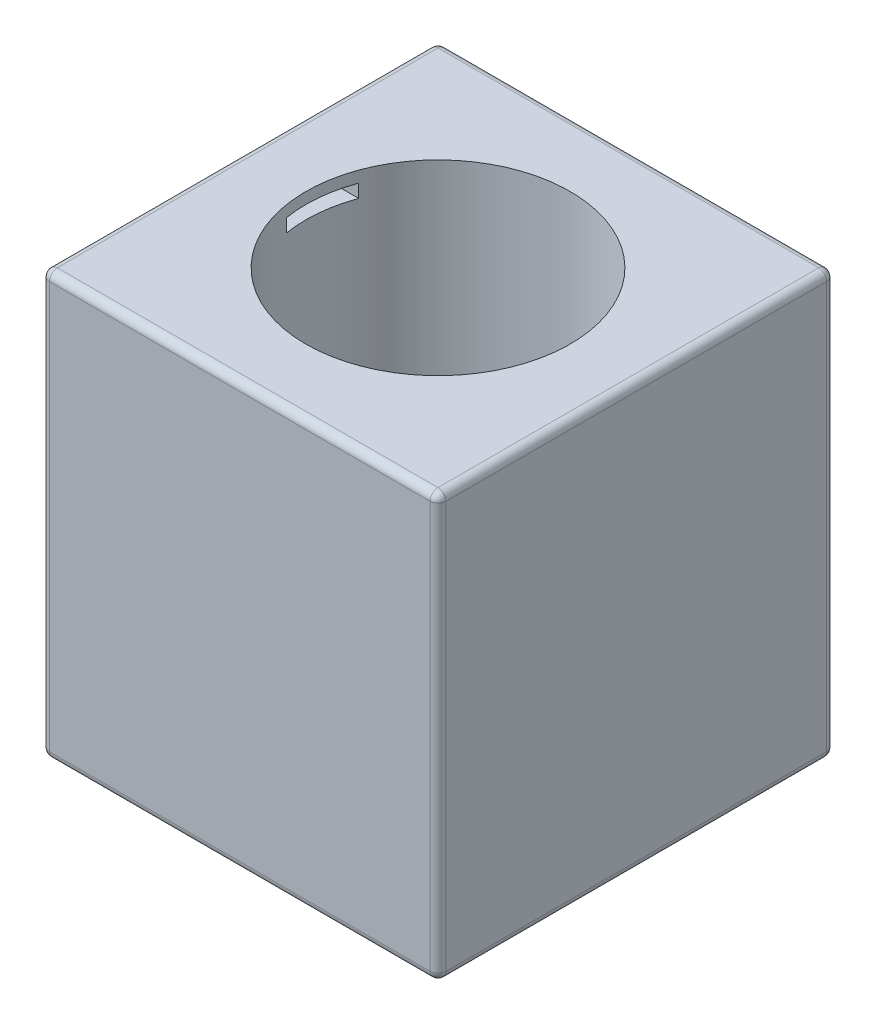
SolidWorks part; units mm, degrees
ref_plane "Front Plane" through (0, 0, 0) normal (0, 0, 1) x (1, 0, 0)
ref_plane "Top Plane" through (0, 0, 0) normal (0, 1, 0) x (1, 0, 0)
ref_plane "Right Plane" through (0, 0, 0) normal (1, 0, 0) x (0, 0, -1)
sketch "Sketch6" plane through (0, 0, 0) normal (0, 1, 0) x (1, 0, 0)
  line L1 (-75, 75) -> (75, 75)
  line L2 (-75, 75) -> (-75, -75)
  line L3 (-75, -75) -> (75, -75)
  line L4 (75, 75) -> (75, -75)
  line L5 (-75, 75) -> (75, -75) construction
  line L6 (-75, -75) -> (75, 75) construction
  circle A0 centre (0, 0) radius 50
  dimension "D1" = 100
  dimension "D2" = 150
  dimension "D3" = 150
extrude "Boss-Extrude4" add sketch "Sketch6" along normal blind 150
sketch "Sketch7" plane through (0, 0, 0) normal (0, -1, 0) x (1, 0, 0)
  line L4 (75, -75) -> (75, 75)
  line L5 (75, 75) -> (-75, 75)
  line L6 (-75, 75) -> (-75, -75)
  line L7 (-75, -75) -> (75, -75)
  line L8 (75, -75) -> (75, 75)
  line L9 (75, 75) -> (-75, 75)
  line L10 (-75, 75) -> (-75, -75)
  line L11 (-75, -75) -> (75, -75)
  dimension "D1" = 0
extrude "Boss-Extrude5" add sketch "Sketch7" along normal blind 10
sketch "Sketch8" plane through (0, 0, 75) normal (0, 0, 1) x (1, 0, 0)
  line L0 (75, 70) -> (-84.6614, 70) construction
  line L1 (75, 150) -> (75, -10) construction
  line L3 (57, 75) -> (62, 75)
  line L4 (57, 75) -> (57, 65)
  line L5 (57, 65) -> (62, 65)
  line L6 (62, 75) -> (62, 65)
  line L7 (57, 75) -> (62, 65) construction
  line L8 (57, 65) -> (62, 75) construction
  point P4 (59.5, 70)
  dimension "D1" = 13
  dimension "D2" = 5
  dimension "D3" = 10
extrude "Cut-Extrude4" cut sketch "Sketch8" against normal through all both and the other way through all
mirror "Mirror4" about plane through (0, 0, 0) normal (1, 0, 0) of "Cut-Extrude4"
sketch "Sketch9" plane through (75, 0, 0) normal (1, 0, 0) x (0, 0, -1)
  line L0 (75, 70) -> (-84.0949, 70) construction
  line L1 (75, 150) -> (75, -10) construction
  line L3 (57, 75) -> (62, 75)
  line L4 (57, 75) -> (57, 65)
  line L5 (57, 65) -> (62, 65)
  line L6 (62, 75) -> (62, 65)
  line L7 (57, 75) -> (62, 65) construction
  line L8 (57, 65) -> (62, 75) construction
  point P4 (59.5, 70)
  dimension "D1" = 5
  dimension "D2" = 10
  dimension "D3" = 13
extrude "Cut-Extrude5" cut sketch "Sketch9" against normal through all both and the other way through all
sketch "Sketch10" plane through (0, 0, -75) normal (0, 0, -1) x (-1, 0, 0)
  line L0 (-108.0476, 70) -> (89.4946, 70) construction
  line L1 (0, 158.7743) -> (0, -29.9585) construction
  line L3 (-24, 85.5) -> (24, 85.5)
  line L4 (-24, 85.5) -> (-24, 54.5)
  line L5 (-24, 54.5) -> (24, 54.5)
  line L6 (24, 85.5) -> (24, 54.5)
  line L7 (-24, 85.5) -> (24, 54.5) construction
  line L8 (-24, 54.5) -> (24, 85.5) construction
  point P4 (0, 70)
  dimension "D1" = 48
  dimension "D2" = 31
extrude "Cut-Extrude6" cut sketch "Sketch10" against normal blind 13 and the other way through all
fillet "Fillet2" radius 3 12 edges at (75, 150, 0) (75, 70, -75) (75, -10, 0) (75, 70, 75) (0, 150, -75) (0, 150, 75) (-75, 150, 0) (-75, -10, 0) (0, -10, -75) (0, -10, 75) (-75, 70, 75) (-75, 70, -75)
sketch "Sketch18" plane through (-75, 0, 0) normal (-1, 0, 0) x (0, 0, 1)
  line L0 (72, 70) -> (-86.1716, 70) construction
  line L1 (72, -7) -> (72, 147) construction
  line L2 (0, 0) -> (0, 147) construction
  line L3 (72, 147) -> (-72, 147) construction
  line L5 (-50, 120) -> (50, 120)
  line L6 (-50, 120) -> (-50, 20)
  line L7 (-50, 20) -> (50, 20)
  line L8 (50, 120) -> (50, 20)
  line L9 (-50, 120) -> (50, 20) construction
  line L10 (-50, 20) -> (50, 120) construction
  point P9 (0, 70)
  dimension "D1" = 100
  dimension "D2" = 100
extrude "Cut-Extrude10" cut sketch "Sketch18" against normal blind 13 contours L5 L8 L7 L6
sketch "Sketch19" plane through (0, 20, 0) normal (0, 1, 0) x (1, 0, 0)
  line L0 (-75, 50) -> (-75, -50) construction
  line L1 (-73, 11.5129) -> (-63, 11.5129)
  line L2 (-73, 11.5129) -> (-73, 1.5129)
  line L3 (-73, 1.5129) -> (-63, 1.5129)
  line L4 (-63, 11.5129) -> (-63, 1.5129)
  line L5 (-73, 11.5129) -> (-63, 1.5129) construction
  line L6 (-73, 1.5129) -> (-63, 11.5129) construction
  point P0 (-68, 6.5129)
  dimension "D1" = 10
  dimension "D2" = 10
  dimension "D3" = 2
extrude "Cut-Extrude11" cut sketch "Sketch19" against normal blind 35
sketch "Sketch21" plane through (0, 120, 0) normal (0, -1, 0) x (1, 0, 0)
  line L0 (-75, -50) -> (-75, 50) construction
  line L1 (-73, -3.8395) -> (-68, -3.8395)
  line L2 (-73, -3.8395) -> (-73, -8.8395)
  line L3 (-73, -8.8395) -> (-68, -8.8395)
  line L4 (-68, -3.8395) -> (-68, -8.8395)
  line L5 (-73, -3.8395) -> (-68, -8.8395) construction
  line L6 (-73, -8.8395) -> (-68, -3.8395) construction
  point P0 (-70.5, -6.3395)
  dimension "D1" = 5
  dimension "D2" = 5
  dimension "D3" = 2
extrude "Cut-Extrude12" cut sketch "Sketch21" against normal blind 25.72
ref_plane "Plane3" through (-42, 0, 0) normal (-1, 0, 0) x (0, 0, 1)
sketch "Sketch23" plane through (-42, 0, 0) normal (-1, 0, 0) x (0, 0, 1)
  line L0 (-72, 147) -> (-72, -7) construction
  line L1 (-17, 145.7222) -> (8, 145.7222)
  line L2 (-17, 145.7222) -> (-17, 140.7222)
  line L3 (-17, 140.7222) -> (8, 140.7222)
  line L4 (8, 145.7222) -> (8, 140.7222)
  line L5 (-17, 145.7222) -> (8, 140.7222) construction
  line L6 (-17, 140.7222) -> (8, 145.7222) construction
  point P4 (-4.5, 143.2222)
  dimension "D1" = 25
  dimension "D2" = 5
  dimension "D3" = 55
extrude "Cut-Extrude13" cut sketch "Sketch23" along normal blind 28
sketch "Sketch24" plane through (0, 0, 75) normal (0, 0, 1) x (1, 0, 0)
  line L0 (-57, 65) -> (-57, 75) construction
  line L1 (-62, 65) -> (-57, 65) construction
  line L2 (-62, 75) -> (-62, 65) construction
  line L3 (-57, 75) -> (-62, 75) construction
  line L4 (62, 65) -> (57, 65) construction
  line L5 (57, 65) -> (57, 75) construction
  line L6 (57, 75) -> (62, 75) construction
  line L7 (62, 75) -> (62, 65) construction
  line L8 (-62, 65) -> (-57, 65)
  line L9 (-62, 75) -> (-62, 65)
  line L10 (-57, 75) -> (-62, 75)
  line L11 (-57, 65) -> (-57, 75)
  line L12 (62, 65) -> (57, 65)
  line L13 (57, 65) -> (57, 75)
  line L14 (57, 75) -> (62, 75)
  line L15 (62, 75) -> (62, 65)
extrude "Boss-Extrude6" add sketch "Sketch24" against normal blind 2
sketch "Sketch27" plane through (0, 0, -75) normal (0, 0, -1) x (-1, 0, 0)
  line L0 (57, 75) -> (57, 65) construction
  line L1 (57, 65) -> (62, 65) construction
  line L2 (62, 65) -> (62, 75) construction
  line L3 (62, 75) -> (57, 75) construction
  line L4 (-62, 75) -> (-62, 65) construction
  line L5 (-62, 65) -> (-57, 65) construction
  line L6 (-57, 65) -> (-57, 75) construction
  line L7 (-57, 75) -> (-62, 75) construction
  line L8 (57, 75) -> (57, 65)
  line L9 (57, 65) -> (62, 65)
  line L10 (62, 65) -> (62, 75)
  line L11 (62, 75) -> (57, 75)
  line L12 (-62, 75) -> (-62, 65)
  line L13 (-62, 65) -> (-57, 65)
  line L14 (-57, 65) -> (-57, 75)
  line L15 (-57, 75) -> (-62, 75)
extrude "Boss-Extrude8" add sketch "Sketch27" against normal blind 2
sketch "Sketch31" plane through (75, 0, 0) normal (1, 0, 0) x (0, 0, -1)
  line L0 (62, 65) -> (57, 65) construction
  line L1 (57, 65) -> (57, 75) construction
  line L2 (62, 75) -> (62, 65) construction
  line L3 (57, 75) -> (62, 75) construction
  line L4 (62, 65) -> (57, 65)
  line L5 (57, 65) -> (57, 75)
  line L6 (62, 75) -> (62, 65)
  line L7 (57, 75) -> (62, 75)
extrude "Boss-Extrude12" add sketch "Sketch31" against normal blind 2
sketch "Sketch32" plane through (-75, 0, 0) normal (-1, 0, 0) x (0, 0, 1)
  line L4 (-62, 75) -> (-62, 65)
  line L5 (-62, 65) -> (-57, 65)
  line L6 (-57, 65) -> (-57, 75)
  line L7 (-57, 75) -> (-62, 75)
  line L8 (-62, 75) -> (-62, 65)
  line L9 (-62, 65) -> (-57, 65)
  line L10 (-57, 65) -> (-57, 75)
  line L11 (-57, 75) -> (-62, 75)
  dimension "D1" = 0
extrude "Boss-Extrude13" add sketch "Sketch32" against normal blind 2
